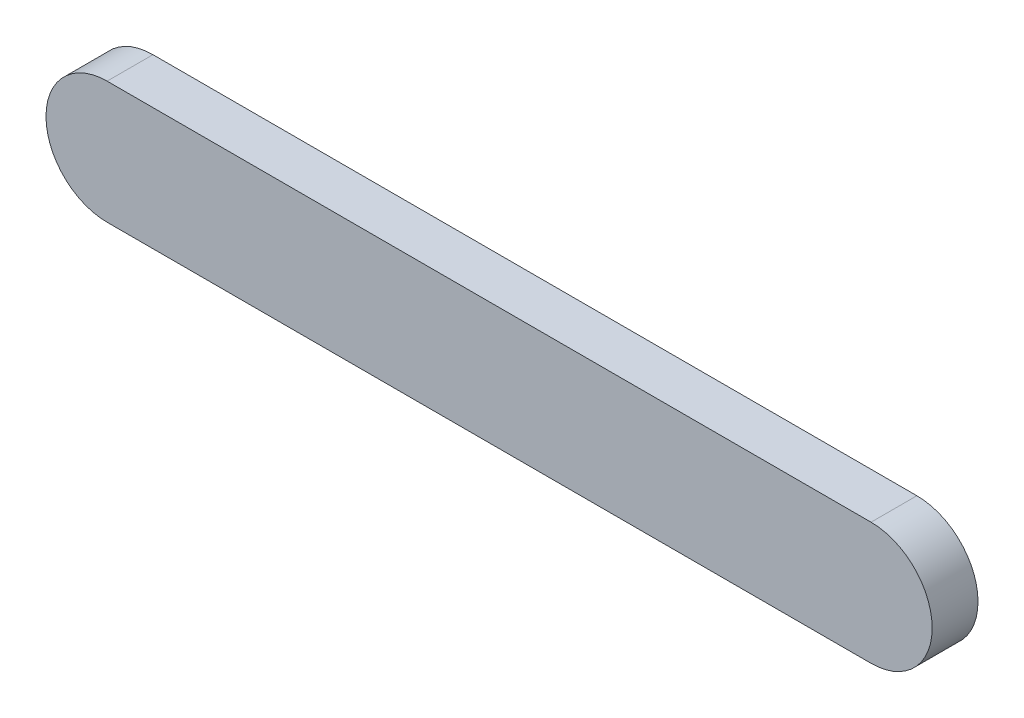
SolidWorks part; units mm, degrees
ref_plane "前视基准面" through (0, 0, 0) normal (0, 0, 1) x (1, 0, 0)
ref_plane "上视基准面" through (0, 0, 0) normal (0, 1, 0) x (1, 0, 0)
ref_plane "右视基准面" through (0, 0, 0) normal (1, 0, 0) x (0, 0, -1)
sketch "草图1" plane through (0, 0, 0) normal (0, 0, 1) x (1, 0, 0)
  line L1 (-10.9276, 3.8465) -> (39.0724, 3.8465)
  line L3 (-10.9276, -4.1535) -> (39.0724, -4.1535)
  arc A0 (-10.9276, 3.8465) -> (-10.9276, -4.1535) centre (-10.9276, -0.1535) ccw
  arc A1 (39.0724, -4.1535) -> (39.0724, 3.8465) centre (39.0724, -0.1535) ccw
  dimension "D1" = 50
  dimension "D2" = 8
extrude "拉伸1" add sketch "草图1" along normal blind 3
